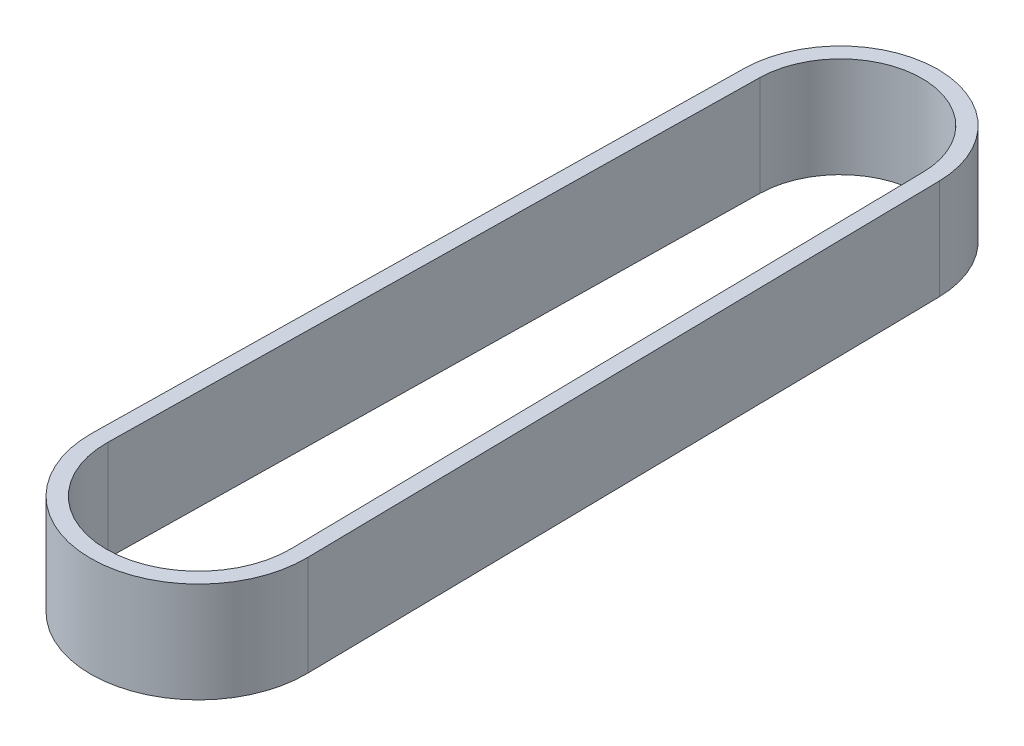
SolidWorks part; units mm, degrees
material "NEOPRENE"
ref_plane "Plan de face" through (0, 0, 0) normal (0, 0, 1) x (1, 0, 0)
ref_plane "Plan de dessus" through (0, 0, 0) normal (0, 1, 0) x (1, 0, 0)
ref_plane "Plan de droite" through (0, 0, 0) normal (1, 0, 0) x (0, 0, -1)
sketch "Esquisse1" plane through (0, 0, 0) normal (0, 1, 0) x (1, 0, 0)
  line L0 (5.8193, -12.4076) -> (5.1743, 28.2173)
  line L1 (-5.1743, 28.2173) -> (-5.8193, -12.4076)
  line L2 (0, 28.1351) -> (0, -12.5) construction
  line L3 (6.8191, -12.3917) -> (6.1742, 28.2331)
  line L4 (-6.1742, 28.2331) -> (-6.8191, -12.3917)
  arc A0 (5.1743, 28.2173) -> (-5.1743, 28.2173) centre (0, 28.1351) ccw
  arc A1 (-5.8193, -12.4076) -> (5.8193, -12.4076) centre (0, -12.5) ccw
  circle A2 centre (0, -12.5) radius 5.82 construction
  circle A3 centre (0, 28.1351) radius 5.175 construction
  arc A4 (6.1742, 28.2331) -> (-6.1742, 28.2331) centre (0, 28.1351) ccw
  arc A5 (-6.8191, -12.3917) -> (6.8191, -12.3917) centre (0, -12.5) ccw
  point P7 (0, 28.1351)
  point P9 (0, 19.0407)
  dimension "D1" = 40.63
  dimension "D2" = 1
extrude "Boss.-Extru.1" add sketch "Esquisse1" along normal mid plane 6.35
